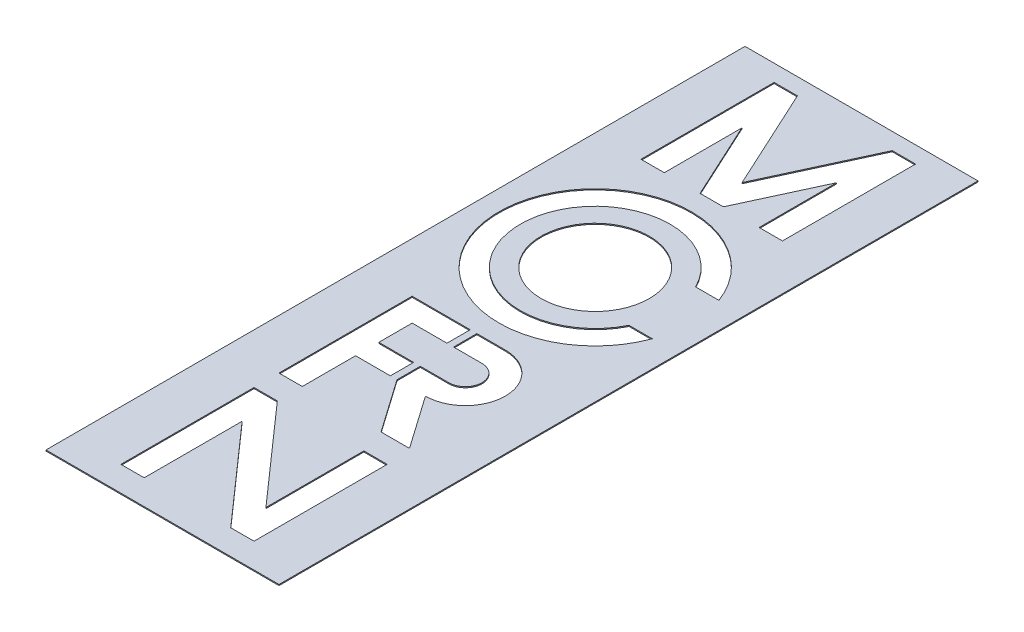
SolidWorks part; units mm, degrees
ref_plane "Front Plane" through (0, 0, 0) normal (0, 0, 1) x (1, 0, 0)
ref_plane "Top Plane" through (0, 0, 0) normal (0, 1, 0) x (1, 0, 0)
ref_plane "Right Plane" through (0, 0, 0) normal (1, 0, 0) x (0, 0, -1)
sketch "Sketch1" plane through (0, 0, 0) normal (0, 1, 0) x (1, 0, 0)
  line L0 (0, 0) -> (0, 50.8)
  line L1 (0, 50.8) -> (8.89, 50.8)
  line L2 (8.89, 50.8) -> (26.9875, 11.5843)
  line L3 (26.9875, 11.5843) -> (45.085, 50.8)
  line L4 (45.085, 50.8) -> (53.975, 50.8)
  line L5 (53.975, 50.8) -> (53.975, 0)
  line L6 (53.975, 0) -> (45.085, 0)
  line L7 (45.085, 0) -> (45.085, 29.5838)
  line L8 (45.085, 29.5838) -> (31.4325, 0)
  line L10 (8.89, 29.5838) -> (8.89, 0)
  line L11 (8.89, 0) -> (0, 0)
  line L12 (8.89, 50.8) -> (45.085, 50.8) construction
  line L13 (26.9875, 50.8) -> (26.9875, 0) construction
  line L14 (31.4325, 0) -> (22.5425, 0)
  line L15 (22.5425, 0) -> (8.89, 29.5838)
  line L16 (0, 10.6828) -> (8.89, 10.6828) construction
  line L17 (12.3642, 22.0555) -> (20.4361, 25.7806) construction
  line L18 (26.9875, 0) -> (26.9875, -209.55) construction
  line L19 (-17.4625, 57.15) -> (71.4375, 57.15)
  line L20 (-17.4625, 57.15) -> (-17.4625, -209.55)
  line L21 (-17.4625, -209.55) -> (71.4375, -209.55)
  line L22 (71.4375, 57.15) -> (71.4375, -209.55)
  line L23 (6.35, -44.45) -> (47.625, -44.45) construction
  line L24 (52.5852, -31.75) -> (61.4752, -31.75)
  line L25 (52.5852, -57.15) -> (61.4752, -57.15)
  line L26 (1.5875, -88.9) -> (1.5875, -139.7)
  line L27 (1.5875, -139.7) -> (10.4775, -139.7)
  line L28 (10.4775, -139.7) -> (10.4775, -119.38)
  line L30 (40.523, -139.7) -> (51.3757, -139.7)
  line L32 (1.5875, -88.9) -> (37.1475, -88.9)
  line L34 (10.4775, -97.79) -> (10.4775, -110.49)
  line L35 (10.4775, -110.49) -> (37.1475, -110.49)
  line L36 (10.4775, -97.79) -> (37.1475, -97.79)
  line L37 (23.8125, -97.79) -> (23.8125, -88.9) construction
  line L38 (1.5875, -104.14) -> (10.4775, -104.14) construction
  line L39 (43.4975, -104.14) -> (52.3875, -104.14) construction
  line L40 (37.1475, -110.49) -> (37.1475, -119.38) construction
  line L41 (39.704, -138.5303) -> (46.9862, -133.4312) construction
  line L42 (51.3757, -139.7) -> (37.1475, -119.38)
  line L44 (26.2948, -119.38) -> (40.523, -139.7)
  line L45 (26.2948, -119.38) -> (10.4775, -119.38)
  line L46 (26.2948, -119.38) -> (37.1475, -119.38) construction
  line L47 (1.5875, -200.025) -> (1.5875, -149.225)
  line L48 (1.5875, -149.225) -> (10.4775, -149.225)
  line L49 (10.4775, -149.225) -> (43.4975, -186.5983)
  line L50 (43.4975, -186.5983) -> (43.4975, -149.225)
  line L51 (43.4975, -149.225) -> (52.3875, -149.225)
  line L52 (52.3875, -149.225) -> (52.3875, -200.025)
  line L53 (52.3875, -200.025) -> (43.4975, -200.025)
  line L54 (43.4975, -200.025) -> (10.4775, -162.6517)
  line L55 (10.4775, -162.6517) -> (10.4775, -200.025)
  line L56 (10.4775, -200.025) -> (1.5875, -200.025)
  line L57 (26.9875, -181.3384) -> (33.6497, -175.4522) construction
  circle A0 centre (26.9875, -44.45) radius 20.6375
  arc A1 (52.5852, -31.75) -> (52.5852, -57.15) centre (26.9875, -44.45) ccw
  arc A2 (61.4752, -31.75) -> (61.4752, -57.15) centre (26.9875, -44.45) ccw
  arc A3 (37.1475, -88.9) -> (37.1475, -119.38) centre (37.1475, -104.14) cw
  arc A4 (37.1475, -97.79) -> (37.1475, -110.49) centre (37.1475, -104.14) cw
  point P17 (26.9875, 0)
  point P71 (-34.788, -190.5)
  point P76 (57.0302, -31.75)
  dimension "D6" = 41.275
  dimension "D7" = 28.575
  dimension "D8" = 8.89
  dimension "D10" = 25.4
  dimension "D1" = 266.7
  dimension "D2" = 50.8
  dimension "D3" = 53.975
  dimension "D4" = 8.89
  dimension "D5" = 6.35
  dimension "D9" = 44.45
  dimension "D11" = 8.89
  dimension "D12" = 50.8
  dimension "D13" = 44.45
  dimension "D14" = 50.8
  dimension "D15" = 12.7
  dimension "D16" = 125
  dimension "D17" = 8.89
  dimension "D18" = 50.8
  dimension "D19" = 50.8
  dimension "D20" = 25.4
  dimension "D21" = 9.525
  dimension "D22" = 25.4
  dimension "D23" = 88.9
extrude "Boss-Extrude1" add sketch "Sketch1" along normal blind 0.4 contours L22 L19 L20 L21 L55 L56 L47 L48 L49 L50 L51 L52 L53 L54 L14 L15 L10 L11 L0 L1 L2 L3 L4 L5 L6 L7 L8 A0 A2 L24 A1 L25 L32 A3 L42 L30 L44 L45 L28 L27 L26 | A4 L36 L34 L35
sketch "Sketch2" plane through (0, 0.4, 0) normal (0, 1, 0) x (1, 0, 0)
  line L0 (1.5875, -88.9) -> (37.1475, -88.9) construction
  line L1 (26.2948, -119.38) -> (23.7548, -119.38)
  line L2 (26.2948, -119.38) -> (26.2948, -88.9)
  line L3 (26.2948, -88.9) -> (23.7548, -88.9)
  line L4 (23.7548, -119.38) -> (23.7548, -88.9)
  dimension "D1" = 2.54
extrude "Boss-Extrude2" add sketch "Sketch2" against normal up to surface (0.4 mm away) up to face at (26.9875, 0, 174.625)
